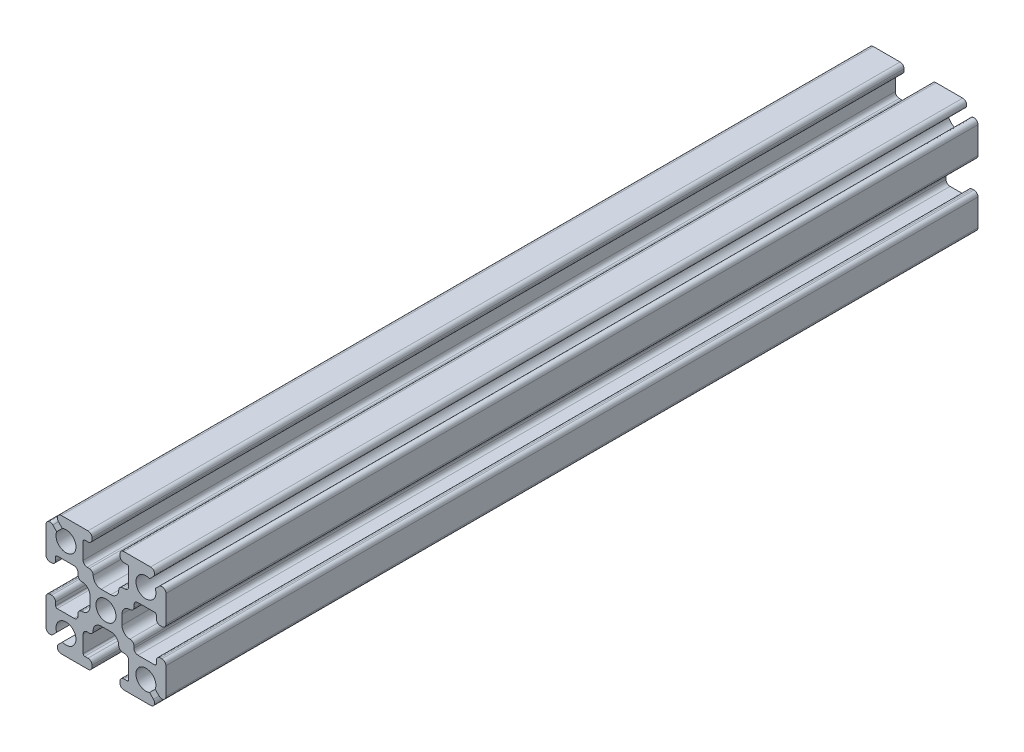
SolidWorks part; units mm, degrees
ref_plane "Front" through (0, 0, 0) normal (0, 0, 1) x (1, 0, 0)
ref_plane "Top" through (0, 0, 0) normal (0, 1, 0) x (1, 0, 0)
ref_plane "Right" through (0, 0, 0) normal (1, 0, 0) x (0, 0, -1)
sketch "Sketch1" plane through (0, 0, 0) normal (0, 0, 1) x (1, 0, 0)
  line L0 (6.6464, 5.9393) -> (6.1636, 5.4565)
  line L1 (5.4565, 6.1636) -> (5.9393, 6.6464)
  line L2 (5.5858, 7.5) -> (2.25, 7.5)
  line L3 (1.75, 7) -> (1.75, 6.8)
  line L4 (2.25, 6.3) -> (2.65, 6.3)
  line L5 (2.85, 6.1) -> (2.85, 4)
  line L6 (2.35, 3.5) -> (2.1, 3.5)
  line L7 (0.6, 2) -> (-0.6, 2)
  line L8 (-2.1, 3.5) -> (-2.35, 3.5)
  line L9 (-2.85, 4) -> (-2.85, 6.1)
  line L10 (-2.65, 6.3) -> (-2.25, 6.3)
  line L11 (-1.75, 6.8) -> (-1.75, 7)
  line L12 (-2.25, 7.5) -> (-5.5858, 7.5)
  line L13 (-5.9393, 6.6464) -> (-5.4565, 6.1636)
  line L14 (-6.1636, 5.4565) -> (-6.6464, 5.9393)
  line L15 (-7.5, 5.5858) -> (-7.5, 2.25)
  line L16 (-7, 1.75) -> (-6.8, 1.75)
  line L17 (-6.3, 2.25) -> (-6.3, 2.65)
  line L18 (-6.1, 2.85) -> (-4, 2.85)
  line L19 (-3.5, 2.35) -> (-3.5, 2.1)
  line L20 (-2, 0.6) -> (-2, -0.6)
  line L21 (-3.5, -2.1) -> (-3.5, -2.35)
  line L22 (-4, -2.85) -> (-6.1, -2.85)
  line L23 (-6.3, -2.65) -> (-6.3, -2.25)
  line L24 (-6.8, -1.75) -> (-7, -1.75)
  line L25 (-7.5, -2.25) -> (-7.5, -5.5858)
  line L26 (-6.6464, -5.9393) -> (-6.1636, -5.4565)
  line L27 (-5.4565, -6.1636) -> (-5.9393, -6.6464)
  line L28 (-5.5858, -7.5) -> (-2.25, -7.5)
  line L29 (-1.75, -7) -> (-1.75, -6.8)
  line L30 (-2.25, -6.3) -> (-2.65, -6.3)
  line L31 (-2.85, -6.1) -> (-2.85, -4)
  line L32 (-2.35, -3.5) -> (-2.1, -3.5)
  line L33 (-0.6, -2) -> (0.6, -2)
  line L34 (2.1, -3.5) -> (2.35, -3.5)
  line L35 (2.85, -4) -> (2.85, -6.1)
  line L36 (2.65, -6.3) -> (2.25, -6.3)
  line L37 (1.75, -6.8) -> (1.75, -7)
  line L38 (2.25, -7.5) -> (5.5858, -7.5)
  line L39 (5.9393, -6.6464) -> (5.4565, -6.1636)
  line L40 (6.1636, -5.4565) -> (6.6464, -5.9393)
  line L41 (7.5, -5.5858) -> (7.5, -2.25)
  line L42 (7, -1.75) -> (6.8, -1.75)
  line L43 (6.3, -2.25) -> (6.3, -2.65)
  line L44 (6.1, -2.85) -> (4, -2.85)
  line L45 (3.5, -2.35) -> (3.5, -2.1)
  line L46 (2, -0.6) -> (2, 0.6)
  line L47 (3.5, 2.1) -> (3.5, 2.35)
  line L48 (4, 2.85) -> (6.1, 2.85)
  line L49 (6.3, 2.65) -> (6.3, 2.25)
  line L50 (6.8, 1.75) -> (7, 1.75)
  line L51 (7.5, 2.25) -> (7.5, 5.5858)
  circle A0 centre (0, 0) radius 1.25
  arc A1 (6.1636, 5.4565) -> (5.4565, 6.1636) centre (5, 5) cw
  arc A2 (5.9393, 6.6464) -> (5.5858, 7.5) centre (5.5858, 7) ccw
  arc A3 (2.25, 7.5) -> (1.75, 7) centre (2.25, 7) ccw
  arc A4 (1.75, 6.8) -> (2.25, 6.3) centre (2.25, 6.8) ccw
  arc A5 (2.65, 6.3) -> (2.85, 6.1) centre (2.65, 6.1) cw
  arc A6 (2.85, 4) -> (2.35, 3.5) centre (2.35, 4) cw
  arc A7 (2.1, 3.5) -> (1.6, 3) centre (2.1, 3) ccw
  arc A8 (1.6, 3) -> (0.6, 2) centre (0.6, 3) cw
  arc A9 (-0.6, 2) -> (-1.6, 3) centre (-0.6, 3) cw
  arc A10 (-1.6, 3) -> (-2.1, 3.5) centre (-2.1, 3) ccw
  arc A11 (-2.35, 3.5) -> (-2.85, 4) centre (-2.35, 4) cw
  arc A12 (-2.85, 6.1) -> (-2.65, 6.3) centre (-2.65, 6.1) cw
  arc A13 (-2.25, 6.3) -> (-1.75, 6.8) centre (-2.25, 6.8) ccw
  arc A14 (-1.75, 7) -> (-2.25, 7.5) centre (-2.25, 7) ccw
  arc A15 (-5.5858, 7.5) -> (-5.9393, 6.6464) centre (-5.5858, 7) ccw
  arc A16 (-5.4565, 6.1636) -> (-6.1636, 5.4565) centre (-5, 5) cw
  arc A17 (-6.6464, 5.9393) -> (-7.5, 5.5858) centre (-7, 5.5858) ccw
  arc A18 (-7.5, 2.25) -> (-7, 1.75) centre (-7, 2.25) ccw
  arc A19 (-6.8, 1.75) -> (-6.3, 2.25) centre (-6.8, 2.25) ccw
  arc A20 (-6.3, 2.65) -> (-6.1, 2.85) centre (-6.1, 2.65) cw
  arc A21 (-4, 2.85) -> (-3.5, 2.35) centre (-4, 2.35) cw
  arc A22 (-3.5, 2.1) -> (-3, 1.6) centre (-3, 2.1) ccw
  arc A23 (-3, 1.6) -> (-2, 0.6) centre (-3, 0.6) cw
  arc A24 (-2, -0.6) -> (-3, -1.6) centre (-3, -0.6) cw
  arc A25 (-3, -1.6) -> (-3.5, -2.1) centre (-3, -2.1) ccw
  arc A26 (-3.5, -2.35) -> (-4, -2.85) centre (-4, -2.35) cw
  arc A27 (-6.1, -2.85) -> (-6.3, -2.65) centre (-6.1, -2.65) cw
  arc A28 (-6.3, -2.25) -> (-6.8, -1.75) centre (-6.8, -2.25) ccw
  arc A29 (-7, -1.75) -> (-7.5, -2.25) centre (-7, -2.25) ccw
  arc A30 (-7.5, -5.5858) -> (-6.6464, -5.9393) centre (-7, -5.5858) ccw
  arc A31 (-6.1636, -5.4565) -> (-5.4565, -6.1636) centre (-5, -5) cw
  arc A32 (-5.9393, -6.6464) -> (-5.5858, -7.5) centre (-5.5858, -7) ccw
  arc A33 (-2.25, -7.5) -> (-1.75, -7) centre (-2.25, -7) ccw
  arc A34 (-1.75, -6.8) -> (-2.25, -6.3) centre (-2.25, -6.8) ccw
  arc A35 (-2.65, -6.3) -> (-2.85, -6.1) centre (-2.65, -6.1) cw
  arc A36 (-2.85, -4) -> (-2.35, -3.5) centre (-2.35, -4) cw
  arc A37 (-2.1, -3.5) -> (-1.6, -3) centre (-2.1, -3) ccw
  arc A38 (-1.6, -3) -> (-0.6, -2) centre (-0.6, -3) cw
  arc A39 (0.6, -2) -> (1.6, -3) centre (0.6, -3) cw
  arc A40 (1.6, -3) -> (2.1, -3.5) centre (2.1, -3) ccw
  arc A41 (2.35, -3.5) -> (2.85, -4) centre (2.35, -4) cw
  arc A42 (2.85, -6.1) -> (2.65, -6.3) centre (2.65, -6.1) cw
  arc A43 (2.25, -6.3) -> (1.75, -6.8) centre (2.25, -6.8) ccw
  arc A44 (1.75, -7) -> (2.25, -7.5) centre (2.25, -7) ccw
  arc A45 (5.5858, -7.5) -> (5.9393, -6.6464) centre (5.5858, -7) ccw
  arc A46 (5.4565, -6.1636) -> (6.1636, -5.4565) centre (5, -5) cw
  arc A47 (6.6464, -5.9393) -> (7.5, -5.5858) centre (7, -5.5858) ccw
  arc A48 (7.5, -2.25) -> (7, -1.75) centre (7, -2.25) ccw
  arc A49 (6.8, -1.75) -> (6.3, -2.25) centre (6.8, -2.25) ccw
  arc A50 (6.3, -2.65) -> (6.1, -2.85) centre (6.1, -2.65) cw
  arc A51 (4, -2.85) -> (3.5, -2.35) centre (4, -2.35) cw
  arc A52 (3.5, -2.1) -> (3, -1.6) centre (3, -2.1) ccw
  arc A53 (3, -1.6) -> (2, -0.6) centre (3, -0.6) cw
  arc A54 (2, 0.6) -> (3, 1.6) centre (3, 0.6) cw
  arc A55 (3, 1.6) -> (3.5, 2.1) centre (3, 2.1) ccw
  arc A56 (3.5, 2.35) -> (4, 2.85) centre (4, 2.35) cw
  arc A57 (6.1, 2.85) -> (6.3, 2.65) centre (6.1, 2.65) cw
  arc A58 (6.3, 2.25) -> (6.8, 1.75) centre (6.8, 2.25) ccw
  arc A59 (7, 1.75) -> (7.5, 2.25) centre (7, 2.25) ccw
  arc A60 (7.5, 5.5858) -> (6.6464, 5.9393) centre (7, 5.5858) ccw
extrude "Boss-Extrude1" add sketch "Sketch1" along normal blind 101.6
